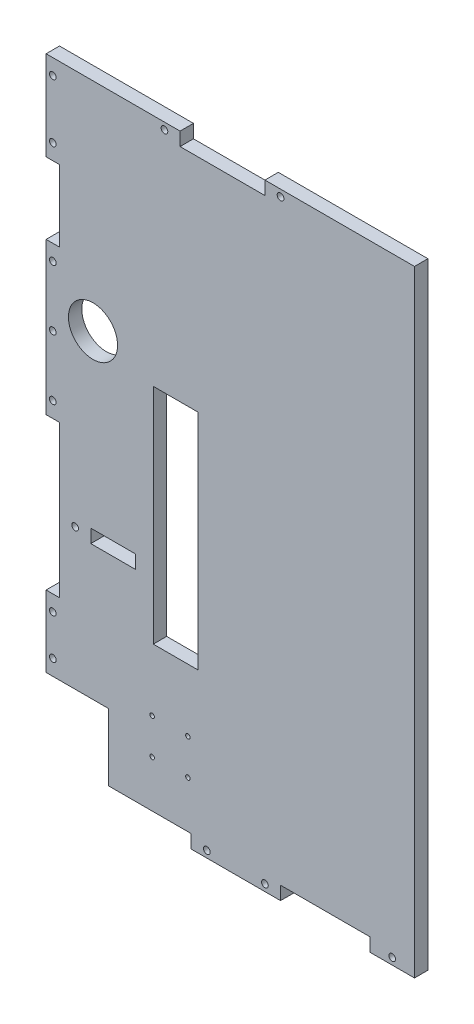
SolidWorks part; units mm, degrees
ref_plane "Plan de face" through (0, 0, 0) normal (0, 0, 1) x (1, 0, 0)
ref_plane "Plan de dessus" through (0, 0, 0) normal (0, 1, 0) x (1, 0, 0)
ref_plane "Plan de droite" through (0, 0, 0) normal (1, 0, 0) x (0, 0, -1)
sketch "Esquisse1" plane through (0, 0, 0) normal (0, 0, 1) x (1, 0, 0)
  line L1 (0, 0) -> (-165, 0)
  line L2 (0, 0) -> (0, 276)
  line L3 (0, 276) -> (-165, 276)
  line L4 (-165, 0) -> (-165, 276)
  dimension "D1" = 276
  dimension "D2" = 165
extrude "Boss.-Extru.1" add sketch "Esquisse1" along normal blind 6
sketch "Esquisse2" plane through (0, 0, 6) normal (0, 0, 1) x (1, 0, 0)
  line L0 (0, 276) -> (-165, 276) construction
  line L8 (0, 276) -> (-165, 276) construction
  line L9 (-165, 0) -> (0, 0) construction
  line L10 (-105, 276) -> (-67, 276)
  line L11 (-105, 276) -> (-105, 270)
  line L12 (-105, 270) -> (-67, 270)
  line L13 (-165, 276) -> (-165, 0) construction
  line L14 (-165, 236) -> (-159, 236)
  line L15 (-165, 236) -> (-165, 204)
  line L16 (-165, 204) -> (-159, 204)
  line L17 (-159, 236) -> (-159, 204)
  line L19 (-165, 136) -> (-159, 136)
  line L20 (-165, 136) -> (-165, 68)
  line L21 (-165, 68) -> (-159, 68)
  line L22 (-159, 136) -> (-159, 68)
  line L23 (-137, 36) -> (-137, 6)
  line L24 (-165, 0) -> (-165, 36)
  line L25 (-165, 36) -> (-137, 36)
  line L26 (-100, 0) -> (-165, 0)
  line L27 (-20, 0) -> (-60, 0)
  line L28 (-20, 0) -> (-20, 6)
  line L29 (-20, 6) -> (-60, 6)
  line L30 (-60, 0) -> (-60, 6)
  line L31 (0, 0) -> (0, 276) construction
  line L33 (-100, 0) -> (-100, 6)
  line L34 (-100, 6) -> (-137, 6)
  line L35 (-67, 276) -> (-67, 270)
  dimension "D1" = 6
  dimension "D2" = 6
  dimension "D3" = 68
  dimension "D4" = 32
  dimension "D5" = 40
  dimension "D6" = 68
  dimension "D7" = 36
  dimension "D8" = 28
  dimension "D9" = 6
  dimension "D10" = 40
  dimension "D11" = 6
  dimension "D12" = 40
  dimension "D13" = 20
  dimension "D14" = 38
  dimension "D15" = 60
  dimension "D16" = 6
extrude "exterieur" cut sketch "Esquisse2" against normal blind 10
sketch "Esquisse3" plane through (0, 0, 6) normal (0, 0, 1) x (1, 0, 0)
  line L0 (-165, 204) -> (-159, 204) construction
  line L1 (-145, 102) -> (-125, 102)
  line L2 (-145, 102) -> (-145, 96)
  line L3 (-145, 96) -> (-125, 96)
  line L4 (-125, 102) -> (-125, 96)
  line L5 (-165, 204) -> (-165, 136) construction
  line L6 (-165, 68) -> (-165, 36) construction
  line L8 (-100, 0) -> (-60, 0) construction
  circle A0 centre (-144, 178.92) radius 11
  dimension "D1" = 22
  dimension "D2" = 20
  dimension "D4" = 21
  dimension "D3" = 6
  dimension "D5" = 25.08
  dimension "D6" = 20
  dimension "D7" = 102
extrude "Enlèv. mat.-Extru.2" cut sketch "Esquisse3" against normal through all
sketch "Esquisse4" plane through (0, 0, 6) normal (0, 0, 1) x (1, 0, 0)
  line L0 (-105, 270) -> (-67, 270) construction
  line L1 (-105, 276) -> (-165, 276) construction
  line L2 (-105, 276) -> (-105, 270) construction
  line L3 (-67, 270) -> (-67, 276) construction
  line L4 (-165, 204) -> (-159, 204) construction
  line L5 (-159, 136) -> (-165, 136) construction
  line L6 (-165, 68) -> (-159, 68) construction
  line L7 (-137, 36) -> (-165, 36) construction
  line L8 (-100, 0) -> (-100, 6) construction
  line L9 (-60, 6) -> (-60, 0) construction
  line L10 (-100, 0) -> (-60, 0) construction
  line L11 (-165, 68) -> (-165, 36) construction
  line L12 (-165, 204) -> (-165, 136) construction
  line L13 (-20, 0) -> (0, 0) construction
  line L14 (-20, 0) -> (-20, 6) construction
  line L15 (-165, 276) -> (-165, 236) construction
  line L16 (-159, 236) -> (-165, 236) construction
  line L17 (-145, 102) -> (-145, 96) construction
  line L18 (-145, 96) -> (-125, 96) construction
  line L19 (-100, 6) -> (-137, 6) construction
  line L20 (-137, 6) -> (-137, 36) construction
  circle A0 centre (-60, 273) radius 1.5
  circle A1 centre (-112, 273) radius 1.5
  circle A2 centre (-162, 197) radius 1.5
  circle A3 centre (-162, 170) radius 1.5
  circle A4 centre (-162, 143) radius 1.5
  circle A5 centre (-162, 61) radius 1.5
  circle A6 centre (-162, 43) radius 1.5
  circle A7 centre (-93, 3) radius 1.5
  circle A8 centre (-67, 3) radius 1.5
  circle A9 centre (-10, 3) radius 1.5
  circle A10 centre (-162, 269) radius 1.5
  circle A11 centre (-162, 243) radius 1.5
  circle A12 centre (-117.5, 27) radius 1.005
  circle A13 centre (-117.5, 43) radius 1.005
  circle A14 centre (-101.5, 43) radius 1.005
  circle A15 centre (-101.5, 27) radius 1.005
  circle A16 centre (-152, 99) radius 1.5
  point P28 (-162, 204)
  point P45 (-165, 170)
  point P46 (-10, 0)
  point P49 (-20, 3)
  point P60 (-162, 236)
  point P81 (-118.5, 6)
  dimension "D1" = 3
  dimension "D2" = 3
  dimension "D3" = 3
  dimension "D4" = 7
  dimension "D5" = 3
  dimension "D6" = 7
  dimension "D7" = 3
  dimension "D8" = 7
  dimension "D9" = 3
  dimension "D10" = 34
  dimension "D11" = 3
  dimension "D12" = 7
  dimension "D13" = 3
  dimension "D14" = 7
  dimension "D15" = 3
  dimension "D16" = 7
  dimension "D17" = 3
  dimension "D18" = 3
  dimension "D19" = 7
  dimension "D20" = 7
  dimension "D21" = 3
  dimension "D22" = 3
  dimension "D23" = 3
  dimension "D24" = 3
  dimension "D25" = 3
  dimension "D26" = 3
  dimension "D27" = 3
  dimension "D28" = 3
  dimension "D29" = 3
  dimension "D30" = 10
  dimension "D31" = 3
  dimension "D32" = 3
  dimension "D33" = 7
  dimension "D34" = 3
  dimension "D35" = 7
  dimension "D36" = 3
  dimension "D37" = 3
  dimension "D38" = 7
  dimension "D39" = 3
  dimension "D45" = 2.01
  dimension "D46" = 2.01
  dimension "D47" = 2.01
  dimension "D48" = 2.01
  dimension "D40" = 16
  dimension "D41" = 16
  dimension "D42" = 16
  dimension "D43" = 21
  dimension "D44" = 19.5
extrude "Enlèv. mat.-Extru.3" cut sketch "Esquisse4" against normal through all
sketch "Esquisse5" plane through (0, 0, 0) normal (0, 0, -1) x (-1, 0, 0)
  circle A0 centre (60, 273) radius 2.995
  circle A1 centre (112, 273) radius 2.995
  circle A2 centre (162, 197) radius 2.995
  circle A3 centre (162, 170) radius 2.995
  circle A4 centre (162, 143) radius 2.995
  circle A5 centre (162, 61) radius 2.995
  circle A6 centre (162, 43) radius 2.995
  circle A7 centre (93, 3) radius 2.995
  circle A8 centre (67, 3) radius 2.995
  circle A9 centre (10, 3) radius 2.995
  circle A10 centre (162, 269) radius 2.995
  circle A11 centre (162, 243) radius 2.995
  circle A12 centre (152, 99) radius 3
  circle A13 centre (117.5, 43) radius 2
  circle A14 centre (117.5, 27) radius 2
  circle A15 centre (101.5, 27) radius 2
  circle A16 centre (101.5, 43) radius 2
  dimension "D1" = 5.99
  dimension "D2" = 5.99
  dimension "D3" = 5.99
  dimension "D4" = 5.99
  dimension "D5" = 5.99
  dimension "D6" = 5.99
  dimension "D7" = 5.99
  dimension "D8" = 5.99
  dimension "D9" = 5.99
  dimension "D10" = 5.99
  dimension "D11" = 5.99
  dimension "D12" = 5.99
  dimension "D13" = 4
  dimension "D14" = 4
  dimension "D15" = 4
  dimension "D16" = 4
  dimension "D17" = 6
extrude "Enlèv. mat.-Extru.4" cut sketch "Esquisse5" against normal blind 3
sketch "Esquisse6" plane through (0, 0, 0) normal (0, 0, -1) x (-1, 0, 0)
  line L0 (165, 204) -> (165, 136) construction
  line L1 (97, 171) -> (117, 171)
  line L2 (97, 171) -> (97, 71)
  line L3 (97, 71) -> (117, 71)
  line L4 (117, 171) -> (117, 71)
  line L5 (100, 6) -> (137, 6) construction
  dimension "D1" = 20
  dimension "D2" = 48
  dimension "D3" = 65
  dimension "D4" = 100
extrude "Enlèv. mat.-Extru.5" cut sketch "Esquisse6" against normal through all
